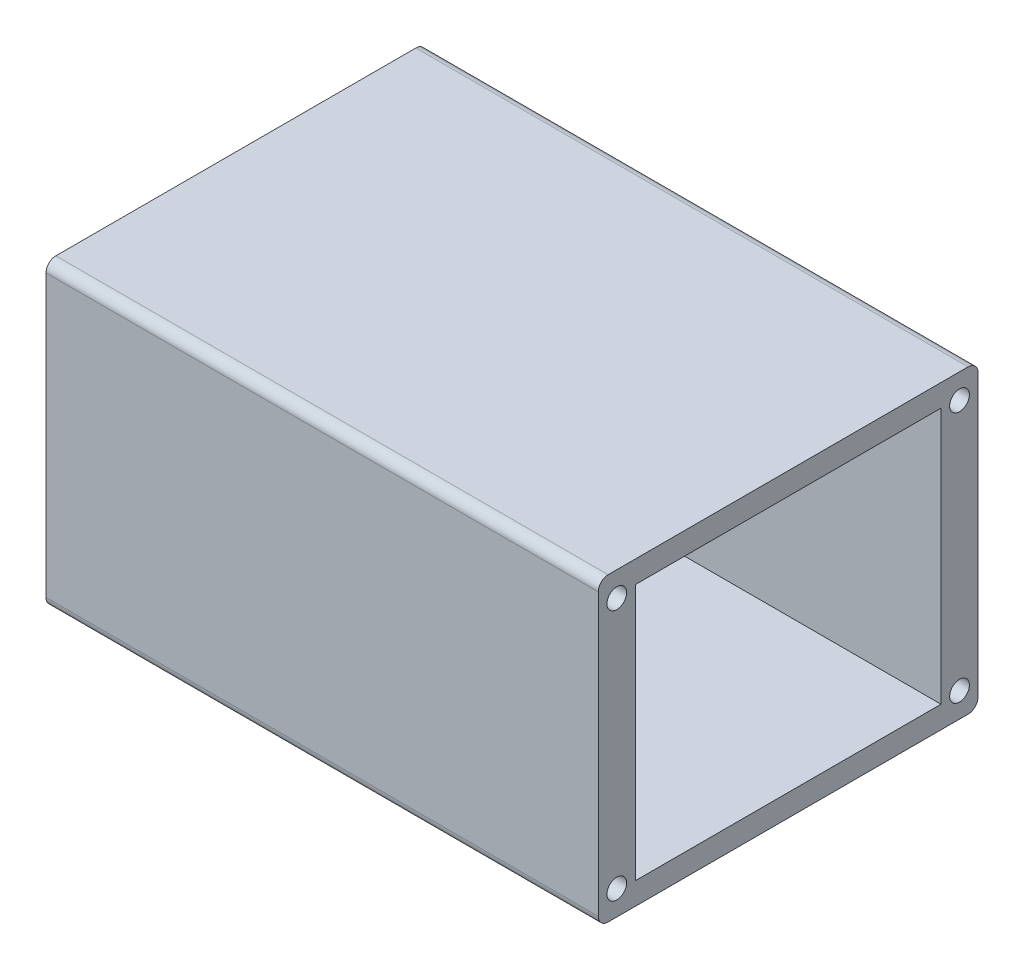
SolidWorks part; units mm, degrees
ref_plane "Alzado" through (0, 0, 0) normal (0, 0, 1) x (1, 0, 0)
ref_plane "Planta" through (0, 0, 0) normal (0, 1, 0) x (1, 0, 0)
ref_plane "Vista lateral" through (0, 0, 0) normal (1, 0, 0) x (0, 0, -1)
sketch "Croquis1" plane through (0, 0, 0) normal (1, 0, 0) x (0, 0, -1)
  line L1 (-38.5, 30.5) -> (38.5, 30.5)
  line L2 (-38.5, 30.5) -> (-38.5, -30.5)
  line L3 (-38.5, -30.5) -> (38.5, -30.5)
  line L4 (38.5, 30.5) -> (38.5, -30.5)
  line L5 (-38.5, 30.5) -> (38.5, -30.5) construction
  line L6 (-38.5, -30.5) -> (38.5, 30.5) construction
  point P0 (0, 0)
  dimension "D1" = 61
  dimension "D2" = 77
extrude "Saliente-Extruir1" add sketch "Croquis1" along normal blind 112
sketch "Croquis3" plane through (112, 0, 0) normal (1, 0, 0) x (0, 0, -1)
  line L1 (-31, 26) -> (31, 26)
  line L2 (-31, 26) -> (-31, -26)
  line L3 (-31, -26) -> (31, -26)
  line L4 (31, 26) -> (31, -26)
  line L5 (-31, 26) -> (31, -26) construction
  line L6 (-31, -26) -> (31, 26) construction
  point P0 (0, 0)
  dimension "D1" = 62
  dimension "D2" = 52
extrude "Cortar-Extruir4" cut sketch "Croquis3" against normal blind 110
sketch "Croquis10" plane through (112, 0, 0) normal (1, 0, 0) x (0, 0, -1)
  line L0 (-31, 26) -> (-31, -26) construction
  line L1 (38.5, 30.5) -> (-38.5, 30.5) construction
  line L2 (-38.5, -30.5) -> (38.5, -30.5) construction
  line L3 (31, -26) -> (31, 26) construction
  circle A0 centre (-34.75, 25.5) radius 2
  circle A2 centre (34.75, 25.5) radius 2
  circle A3 centre (34.75, -25.5) radius 2
  circle A4 centre (-34.75, -25.5) radius 2
  point P0 (-34.75, 25.5)
  dimension "D3" = 4
  dimension "D4" = 4
  dimension "D6" = 4
  dimension "D8" = 4
  dimension "D1" = 3.75
  dimension "D2" = 5
  dimension "D7" = 3.75
  dimension "D9" = 5
  dimension "D10" = 5
extrude "Cortar-Extruir5" cut sketch "Croquis10" against normal blind 15
fillet "Redondeo1" radius 2 1 edges at (56, 30.5, 38.5)
fillet "Redondeo2" radius 2 3 edges at (56, -30.5, 38.5) (56, -30.5, -38.5) (56, 30.5, -38.5)
